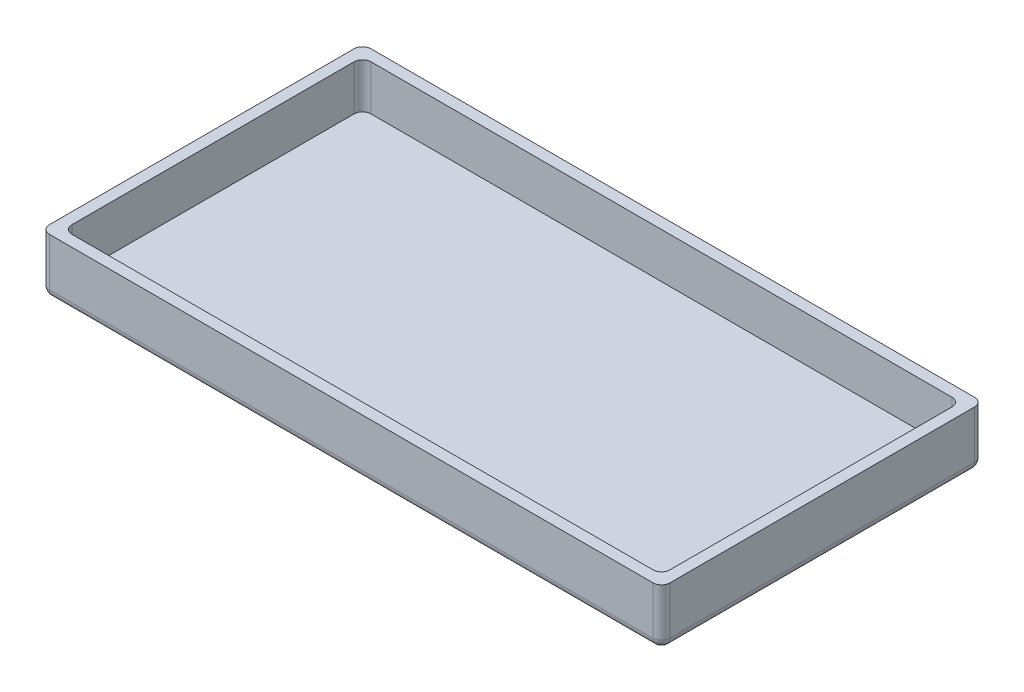
SolidWorks part; units mm, degrees
ref_plane "Front Plane" through (0, 0, 0) normal (0, 0, 1) x (1, 0, 0)
ref_plane "Top Plane" through (0, 0, 0) normal (0, 1, 0) x (1, 0, 0)
ref_plane "Right Plane" through (0, 0, 0) normal (1, 0, 0) x (0, 0, -1)
sketch "Sketch1" plane through (0, 0, 0) normal (0, 1, 0) x (1, 0, 0)
  line L1 (-53, -26.5) -> (53, -26.5)
  line L2 (-53, -26.5) -> (-53, 26.5)
  line L3 (-53, 26.5) -> (53, 26.5)
  line L4 (53, -26.5) -> (53, 26.5)
  line L5 (-53, -26.5) -> (53, 26.5) construction
  line L6 (-53, 26.5) -> (53, -26.5) construction
  point P0 (0, 0)
  dimension "D1" = 53
  dimension "D2" = 106
extrude "Extrude-Thin1" add sketch "Sketch1" along normal blind 10 thin
sketch "Sketch2" plane through (0, 0, 0) normal (0, 1, 0) x (1, 0, 0)
  line L1 (-55, -28.5) -> (55, -28.5)
  line L2 (-55, -28.5) -> (-55, 28.5)
  line L3 (-55, 28.5) -> (55, 28.5)
  line L4 (55, -28.5) -> (55, 28.5)
  line L5 (-55, -28.5) -> (55, 28.5) construction
  line L6 (-55, 28.5) -> (55, -28.5) construction
  point P0 (0, 0)
extrude "Boss-Extrude1" add sketch "Sketch2" along normal blind 2
fillet "Fillet1" radius 1.5 12 edges at (53, 6, 26.5) (-53, 6, 26.5) (-53, 6, -26.5) (53, 6, -26.5) (55, 0, 0) (0, 0, -28.5) (55, 5, 28.5) (-55, 5, 28.5) (-55, 5, -28.5) (55, 5, -28.5) (-55, 0, 0) (0, 0, 28.5)
sketch "Sketch4" plane through (0, 0, 0) normal (0, -1, 0) x (-1, 0, 0)
  text T0 "<b>BICYCLE e-KIT</b>"
extrude "Cut-Extrude1" cut sketch "Sketch4" against normal blind 0.75
